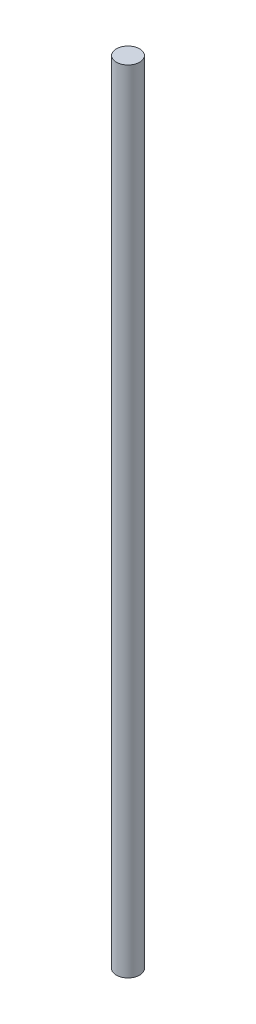
SolidWorks part; units mm, degrees
ref_plane "Front Plane" through (0, 0, 0) normal (0, 0, 1) x (1, 0, 0)
ref_plane "Top Plane" through (0, 0, 0) normal (0, 1, 0) x (1, 0, 0)
ref_plane "Right Plane" through (0, 0, 0) normal (1, 0, 0) x (0, 0, -1)
sketch "Sketch1" plane through (0, 0, 0) normal (0, 1, 0) x (1, 0, 0)
  circle A0 centre (0, 0) radius 2.5
  dimension "D1" = 5
extrude "Boss-Extrude1" add sketch "Sketch1" along normal blind 170
